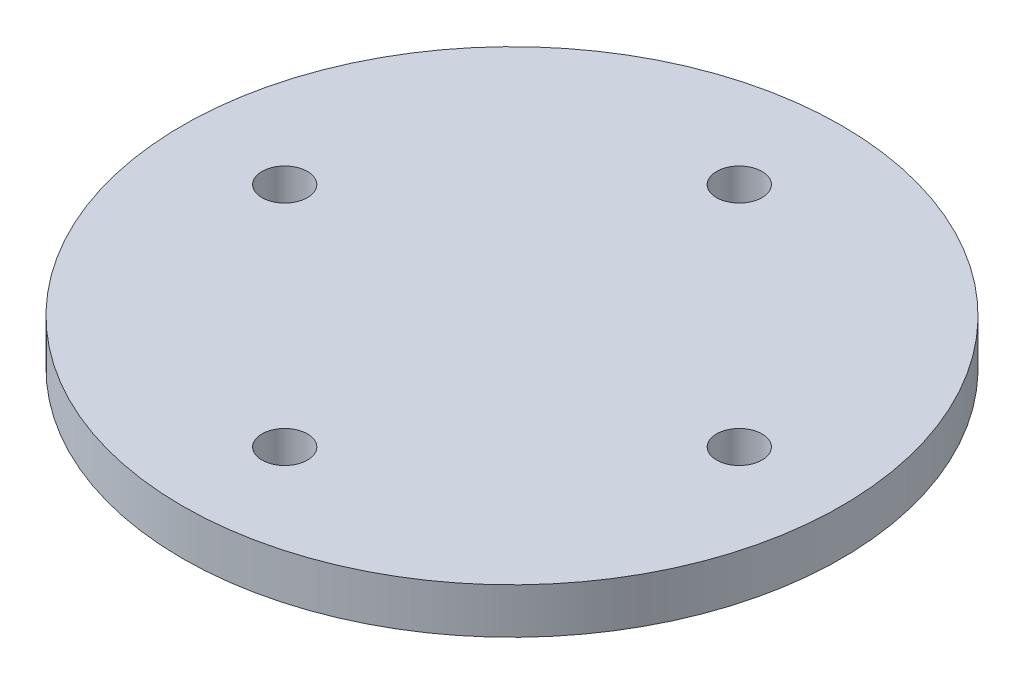
SolidWorks part; units mm, degrees
material "eSUN Tough Resin"
ref_plane "Front Plane" through (0, 0, 0) normal (0, 0, 1) x (1, 0, 0)
ref_plane "Top Plane" through (0, 0, 0) normal (0, 1, 0) x (1, 0, 0)
ref_plane "Right Plane" through (0, 0, 0) normal (1, 0, 0) x (0, 0, -1)
sketch "Sketch1" plane through (0, 0, 0) normal (0, 1, 0) x (1, 0, 0)
  circle A0 centre (0, 0) radius 14.5
  dimension "D1" = 29
extrude "Boss-Extrude1" add sketch "Sketch1" along normal blind 2
sketch "Sketch2" plane through (0, 2, 0) normal (0, 1, 0) x (1, 0, 0)
  circle A0 centre (0, 0) radius 10 construction
  circle A1 centre (0, 10) radius 1.2205
  circle A2 centre (10, 0) radius 1.2205
  circle A3 centre (0, -10) radius 1.2205
  circle A4 centre (-10, 0) radius 1.2205
  point P2 (0, 10)
  point P8 (10, 0)
  point P10 (0, -10)
  point P12 (-10, 0)
  point P14 (0, 0)
  dimension "D1" = 20
  dimension "D2" = 4
hole_wizard "Ø2.0mm Dowel Hole1" positions "Sketch2" profile "Sketch3" hole size "Ø2.0" standard "ANSI Metric"
sketch "Sketch3" plane through (-10, 2, 0) normal (1, 0, 0) x (0, 0, 1)
  line L0 (0, 0) -> (0, 43.5309)
  line L1 (0, 43.5309) -> (1, 42.93)
  line L2 (1, 42.93) -> (1, 0)
  line L5 (1, 0) -> (0, 0)
  line L10 (0, 43.5309) -> (-1, 42.93) construction
  line L11 (0, -6.35) -> (0, 107.95) construction
  dimension "Hole Dia." = 2
  dimension "Hole Depth" = 42.93
  dimension "Drill Angle" = 118
